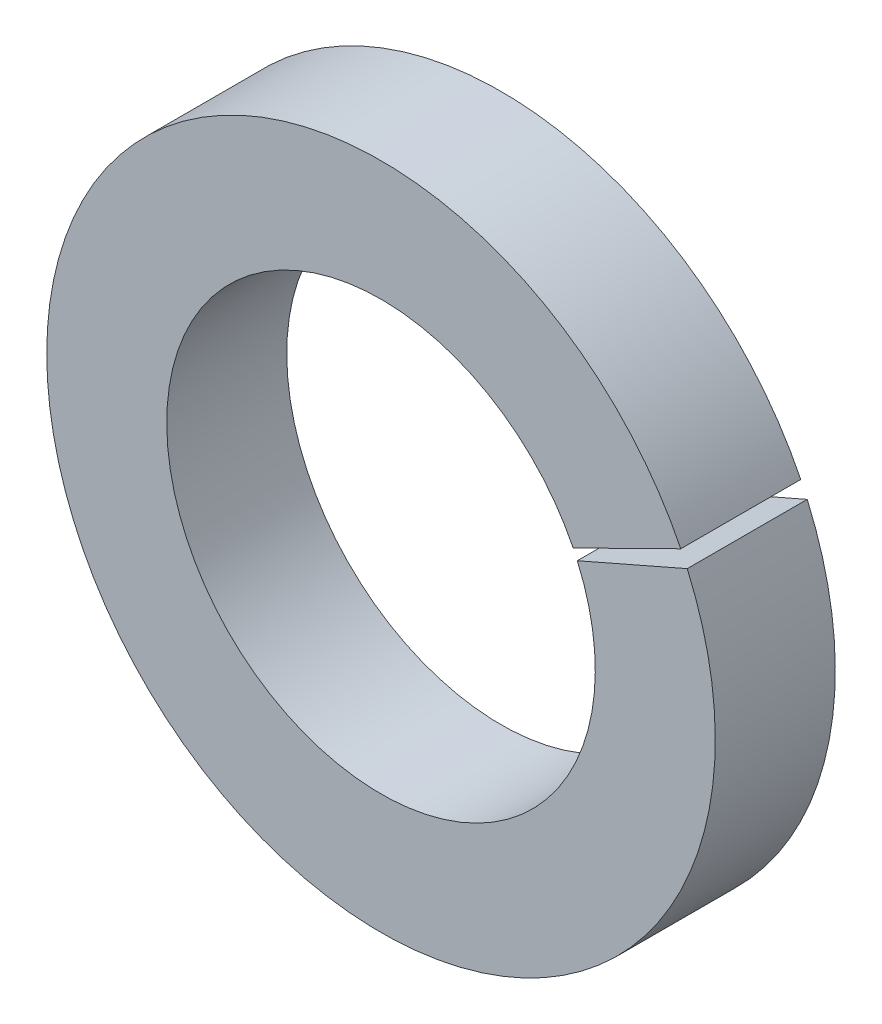
SolidWorks part; units mm, degrees
ref_plane "前视基准面" through (0, 0, 0) normal (0, 0, 1) x (1, 0, 0)
ref_plane "上视基准面" through (0, 0, 0) normal (0, 1, 0) x (1, 0, 0)
ref_plane "右视基准面" through (0, 0, 0) normal (1, 0, 0) x (0, 0, -1)
sketch "草图1" plane through (0, 0, 0) normal (0, 0, 1) x (1, 0, 0)
  circle A0 centre (0, 0) radius 3.9
  circle A1 centre (0, 0) radius 2.5
  dimension "D1" = 5
  dimension "D2" = 7.8
extrude "凸台-拉伸1" add sketch "草图1" along normal blind 1.4
sketch "草图2" plane through (0, 0, 1.4) normal (0, 0, 1) x (1, 0, 0)
  line L0 (0, 0) -> (4.8125, 2.3756)
  line L1 (4.8125, 2.3756) -> (4.8125, 2.1059)
  line L2 (4.8125, 2.1059) -> (0, 0)
extrude "切除-拉伸1" cut sketch "草图2" against normal blind 10
